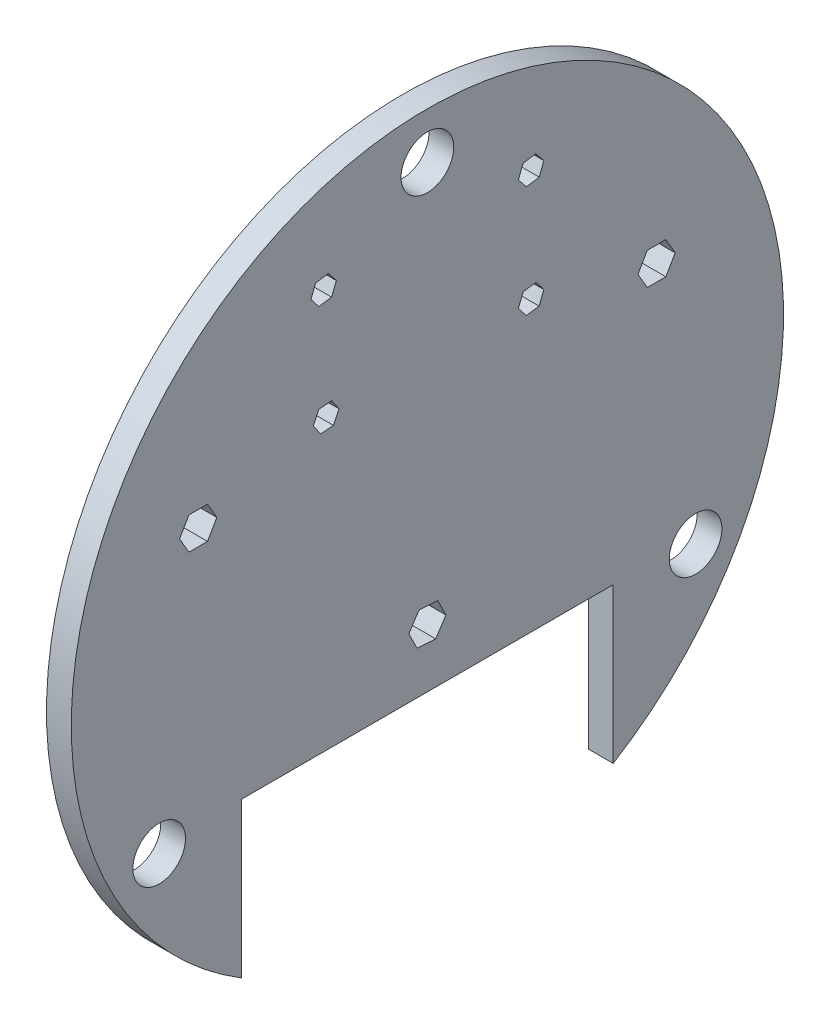
SolidWorks part; units mm, degrees
ref_plane "Ebene vorne" through (0, 0, 0) normal (0, 0, 1) x (1, 0, 0)
ref_plane "Ebene oben" through (0, 0, 0) normal (0, 1, 0) x (1, 0, 0)
ref_plane "Ebene rechts" through (0, 0, 0) normal (1, 0, 0) x (0, 0, -1)
sketch "Sketch1" plane through (0, 0, 0) normal (1, 0, 0) x (0, 0, -1)
  circle A0 centre (0, 0) radius 57.5
  dimension "D1" = 115
extrude "Boss-Extrude1" add sketch "Sketch1" along normal blind 4
sketch "Sketch2" plane through (0, 0, 0) normal (-1, 0, 0) x (0, 0, 1)
  circle A1 centre (0, 50) radius 4.25
  circle A2 centre (43.3013, -25) radius 4.25
  circle A3 centre (-43.3013, -25) radius 4.25
  point P9 (0, 0)
  point P13 (0, 0)
  dimension "D4" = 3
  dimension "D2" = 50
extrude "Cut-Extrude1" cut sketch "Sketch2" against normal through all
sketch "Sketch3" plane through (0, 0, 0) normal (-1, 0, 0) x (0, 0, 1)
  line L0 (-30, -49.0535) -> (-30, -24.0535)
  line L1 (0, 57.5) -> (0, -57.5) construction
  line L2 (30, -49.0535) -> (30, -24.0535)
  line L3 (-30, -24.0535) -> (30, -24.0535)
  circle A0 centre (0, 0) radius 57.5 construction
  arc A2 (-30, -49.0535) -> (30, -49.0535) centre (0, 0) ccw
  dimension "D1" = 25
  dimension "D2" = 60
extrude "Cut-Extrude2" cut sketch "Sketch3" against normal through all
sketch "Sketch4" plane through (4, 0, 0) normal (1, 0, 0) x (0, 0, -1)
  line L1 (15.9993, 38.5783) -> (18.0532, 38.8973)
  line L2 (18.0532, 38.8973) -> (18.8038, 40.8355)
  line L3 (18.8038, 40.8355) -> (17.5007, 42.4546)
  line L4 (17.5007, 42.4546) -> (15.4468, 42.1357)
  line L5 (15.4468, 42.1357) -> (14.6962, 40.1975)
  line L6 (14.6962, 40.1975) -> (15.9993, 38.5783)
  line L7 (-17.5247, 38.5878) -> (-15.4671, 38.8812)
  line L8 (-15.4671, 38.8812) -> (-14.6924, 40.8099)
  line L9 (-14.6924, 40.8099) -> (-15.9753, 42.4452)
  line L10 (-15.9753, 42.4452) -> (-18.0329, 42.1517)
  line L11 (-18.0329, 42.1517) -> (-18.8076, 40.2231)
  line L12 (-18.8076, 40.2231) -> (-17.5247, 38.5878)
  line L13 (15.9753, 20.5878) -> (18.0329, 20.8812)
  line L14 (18.0329, 20.8812) -> (18.8076, 22.8099)
  line L15 (18.8076, 22.8099) -> (17.5247, 24.4452)
  line L16 (17.5247, 24.4452) -> (15.4671, 24.1517)
  line L17 (15.4671, 24.1517) -> (14.6924, 22.2231)
  line L18 (14.6924, 22.2231) -> (15.9753, 20.5878)
  line L19 (-17.2453, 20.6465) -> (-15.173, 20.806)
  line L20 (-15.173, 20.806) -> (-14.2749, 22.6805)
  line L21 (-14.2749, 22.6805) -> (-15.4492, 24.3954)
  line L22 (-15.4492, 24.3954) -> (-17.5216, 24.2359)
  line L23 (-17.5216, 24.2359) -> (-18.4196, 22.3615)
  line L24 (-18.4196, 22.3615) -> (-17.2453, 20.6465)
  line L25 (33.9978, 17.3421) -> (35.4989, 14.7421)
  line L26 (35.4989, 14.7421) -> (38.5011, 14.7421)
  line L27 (38.5011, 14.7421) -> (40.0022, 17.3421)
  line L28 (40.0022, 17.3421) -> (38.5011, 19.9421)
  line L29 (38.5011, 19.9421) -> (35.4989, 19.9421)
  line L30 (35.4989, 19.9421) -> (33.9978, 17.3421)
  line L31 (-40.0022, 17.3421) -> (-38.5011, 14.7421)
  line L32 (-38.5011, 14.7421) -> (-35.4989, 14.7421)
  line L33 (-35.4989, 14.7421) -> (-33.9978, 17.3421)
  line L34 (-33.9978, 17.3421) -> (-35.4989, 19.9421)
  line L35 (-35.4989, 19.9421) -> (-38.5011, 19.9421)
  line L36 (-38.5011, 19.9421) -> (-40.0022, 17.3421)
  line L37 (-1.6574, -17.1163) -> (1.3392, -17.3)
  line L38 (1.3392, -17.3) -> (2.9966, -14.7967)
  line L39 (2.9966, -14.7967) -> (1.6574, -12.1097)
  line L40 (1.6574, -12.1097) -> (-1.3392, -11.926)
  line L41 (-1.3392, -11.926) -> (-2.9966, -14.4293)
  line L42 (-2.9966, -14.4293) -> (-1.6574, -17.1163)
  circle A0 centre (37, 17.3421) radius 2.6 construction
  circle A1 centre (-16.75, 40.5165) radius 1.8 construction
  circle A2 centre (-37, 17.3421) radius 2.6 construction
  circle A3 centre (0, -14.613) radius 2.6 construction
  circle A7 centre (16.75, 40.5165) radius 1.8 construction
  circle A8 centre (16.75, 22.5165) radius 1.8 construction
  circle A9 centre (-16.3473, 22.521) radius 1.8 construction
  dimension "D1" = 5.2
  dimension "D2" = 5.2
  dimension "D3" = 3.6
  dimension "D4" = 3.6
extrude "Cut-Extrude3" cut sketch "Sketch4" against normal through all
